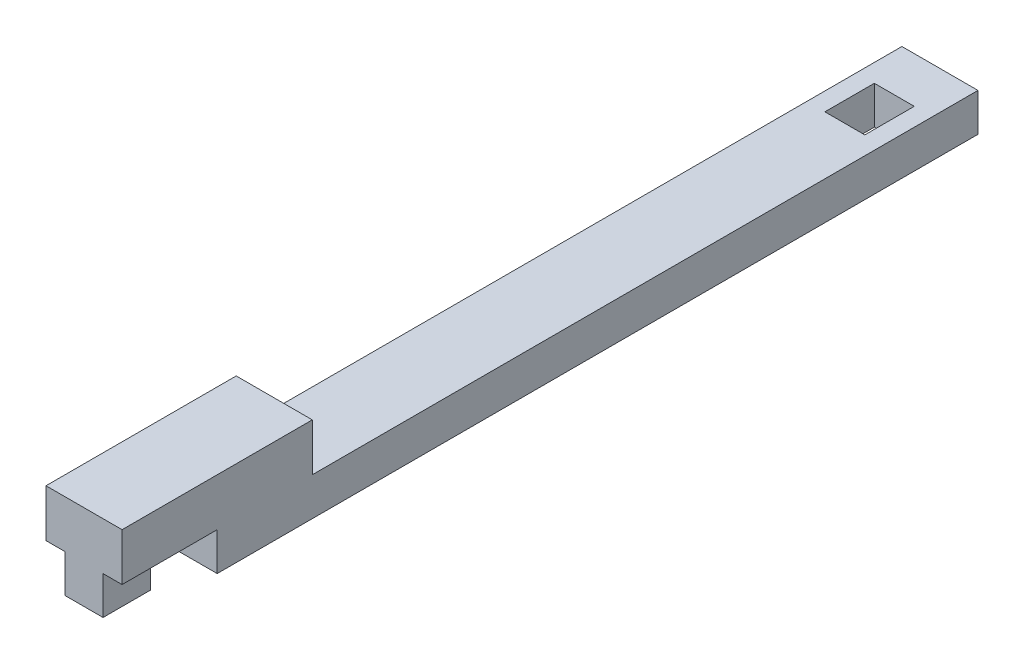
SolidWorks part; units mm, degrees
ref_plane "前视基准面" through (0, 0, 0) normal (0, 0, 1) x (1, 0, 0)
ref_plane "上视基准面" through (0, 0, 0) normal (0, 1, 0) x (1, 0, 0)
ref_plane "右视基准面" through (0, 0, 0) normal (1, 0, 0) x (0, 0, -1)
sketch "草图1" plane through (0, 0, 0) normal (0, 1, 0) x (1, 0, 0)
  line L1 (0, 0) -> (16, 0)
  line L2 (0, 0) -> (0, 160)
  line L3 (0, 160) -> (16, 160)
  line L4 (16, 0) -> (16, 160)
  dimension "D1" = 160
  dimension "D2" = 16
extrude "凸台-拉伸1" add sketch "草图1" along normal blind 8
sketch "草图2" plane through (0, 8, 0) normal (0, 1, 0) x (1, 0, 0)
  line L0 (16, 0) -> (16, 160) construction
  line L1 (0, 0) -> (16, 0)
  line L2 (0, 0) -> (0, 20)
  line L3 (0, 20) -> (16, 20)
  line L4 (16, 0) -> (16, 20)
  dimension "D1" = 20
extrude "凸台-拉伸2" add sketch "草图2" along normal blind 10
sketch "草图3" plane through (0, 0, 0) normal (0, 0, 1) x (1, 0, 0)
  line L0 (16, 18) -> (16, 0) construction
  line L1 (0, 18) -> (16, 18)
  line L2 (0, 18) -> (0, 8)
  line L3 (0, 8) -> (16, 8)
  line L4 (16, 18) -> (16, 8)
  dimension "D1" = 10
extrude "凸台-拉伸3" add sketch "草图3" along normal blind 20
sketch "草图4" plane through (0, 8, 0) normal (0, -1, 0) x (1, 0, 0)
  line L0 (0, 20) -> (16, 20) construction
  line L1 (4, 20) -> (12, 20)
  line L2 (4, 20) -> (4, 10)
  line L3 (4, 10) -> (12, 10)
  line L4 (12, 20) -> (12, 10)
  line L5 (16, 20) -> (16, 0) construction
  dimension "D1" = 10
  dimension "D2" = 8
  dimension "D3" = 4
extrude "凸台-拉伸4" add sketch "草图4" along normal blind 8
sketch "草图5" plane through (0, 8, 0) normal (0, 1, 0) x (1, 0, 0)
  line L0 (0, 140) -> (16, 140)
  line L1 (0, 160) -> (0, 20) construction
  line L2 (16, 20) -> (16, 160) construction
  line L3 (16, 160) -> (0, 160) construction
  line L5 (3.8, 140) -> (12.2, 140)
  line L6 (3.8, 140) -> (3.8, 150.4)
  line L7 (3.8, 150.4) -> (12.2, 150.4)
  line L8 (12.2, 140) -> (12.2, 150.4)
  dimension "D1" = 20
  dimension "D2" = 3.8
  dimension "D3" = 8.4
  dimension "D4" = 10.4
extrude "切除-拉伸1" cut sketch "草图5" against normal through all contours L0 L8 L7 L6
